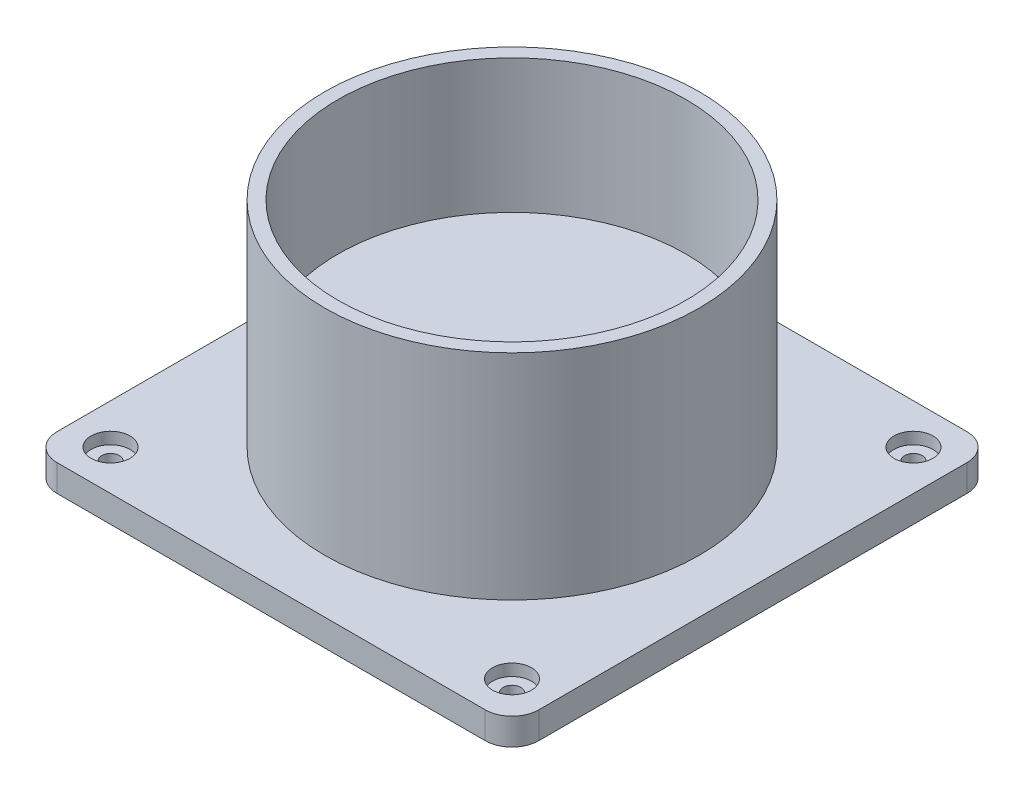
SolidWorks part; units mm, degrees
ref_plane "Front Plane" through (0, 0, 0) normal (0, 0, 1) x (1, 0, 0)
ref_plane "Top Plane" through (0, 0, 0) normal (0, 1, 0) x (1, 0, 0)
ref_plane "Right Plane" through (0, 0, 0) normal (1, 0, 0) x (0, 0, -1)
sketch "Sketch4" plane through (0, 0, 0) normal (0, 1, 0) x (1, 0, 0)
  line L1 (-90, -90) -> (90, -90)
  line L2 (-90, -90) -> (-90, 90)
  line L3 (-90, 90) -> (90, 90)
  line L4 (90, -90) -> (90, 90)
  line L5 (-90, -90) -> (90, 90) construction
  line L6 (-90, 90) -> (90, -90) construction
  point P0 (0, 0)
  dimension "D1" = 180
extrude "Boss-Extrude2" add sketch "Sketch4" along normal blind 10
sketch "Sketch5" plane through (0, 10, 0) normal (0, 1, 0) x (1, 0, 0)
  circle A0 centre (0, 0) radius 70
  dimension "D1" = 140
extrude "Boss-Extrude3" add sketch "Sketch5" along normal blind 80
sketch "Sketch7" plane through (0, 90, 0) normal (0, 1, 0) x (1, 0, 0)
  circle A2 centre (0, 0) radius 65
  circle A3 centre (0, 0) radius 65
  dimension "D1" = 5
extrude "Cut-Extrude1" cut sketch "Sketch7" against normal blind 50
hole_wizard "CBORE for M6 Hex Head Bolt2" positions "Sketch12" profile "Sketch13" counterbore size "M6" standard "ANSI Metric" end condition through all
sketch "Sketch12" plane through (0, 10, 0) normal (0, 1, 0) x (1, 0, 0)
  point P0 (-75, 75)
  point P2 (75, 75)
  point P4 (75, -75)
  point P6 (-75, -75)
  dimension "D1" = 150
  dimension "D2" = 150
  dimension "D3" = 150
  dimension "D4" = 75
  dimension "D5" = 75
sketch "Sketch13" plane through (-75, 10, -75) normal (1, 0, 0) x (0, 0, 1)
  line L0 (0, 0) -> (0, 10)
  line L1 (0, 10) -> (3.3, 10)
  line L3 (3.3, 10) -> (3.3, 4.38)
  line L4 (3.3, 4.38) -> (7.275, 4.38)
  line L5 (7.275, 4.38) -> (7.275, 0)
  line L7 (7.275, 0) -> (0, 0)
  line L11 (0, -6.35) -> (0, 107.95) construction
  dimension "Thru Hole Dia." = 6.6
  dimension "Thru Hole Depth" = 10
  dimension "C'Bore Dia." = 14.55
  dimension "C'Bore Depth" = 4.38
fillet "Fillet1" radius 10 4 edges at (90, 5, 90) (-90, 5, -90) (90, 5, -90) (-90, 5, 90)
